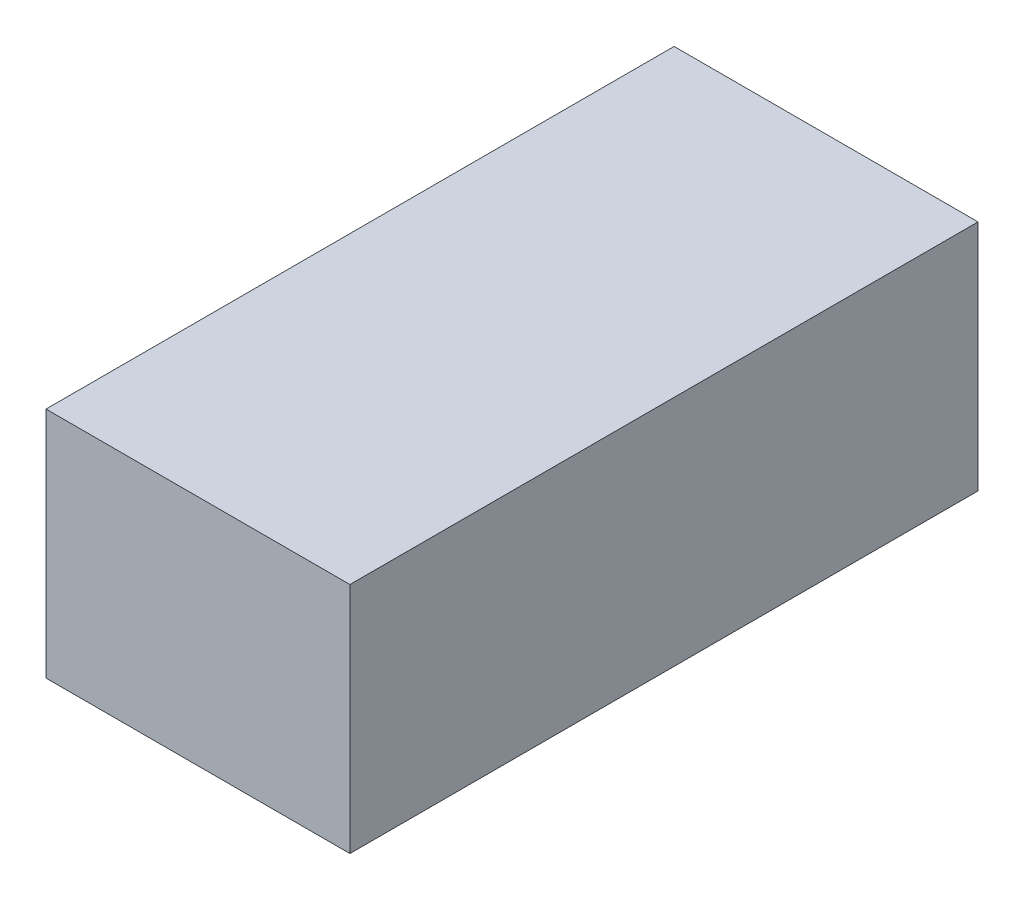
SolidWorks part; units mm, degrees
ref_plane "前视基准面" through (0, 0, 0) normal (0, 0, 1) x (1, 0, 0)
ref_plane "上视基准面" through (0, 0, 0) normal (0, 1, 0) x (1, 0, 0)
ref_plane "右视基准面" through (0, 0, 0) normal (1, 0, 0) x (0, 0, -1)
sketch "草图1" plane through (0, 0, 0) normal (0, 0, 1) x (1, 0, 0)
  line L0 (0, 31.5549) -> (0, -26.0671) construction
  line L1 (-32.9268, 0) -> (32.7439, 0) construction
  line L2 (-15, -11.5) -> (-15, 11.5)
  line L3 (-15, 11.5) -> (15, 11.5)
  line L4 (-15, -11.5) -> (15, -11.5)
  line L5 (15, -11.5) -> (15, 11.5)
  point P5 (15, 0)
  point P10 (-15, 0)
  point P12 (0, -11.5)
  point P13 (0, 11.5)
  dimension "D1" = 30
  dimension "D2" = 23
extrude "凸台-拉伸1" add sketch "草图1" along normal mid plane 62
